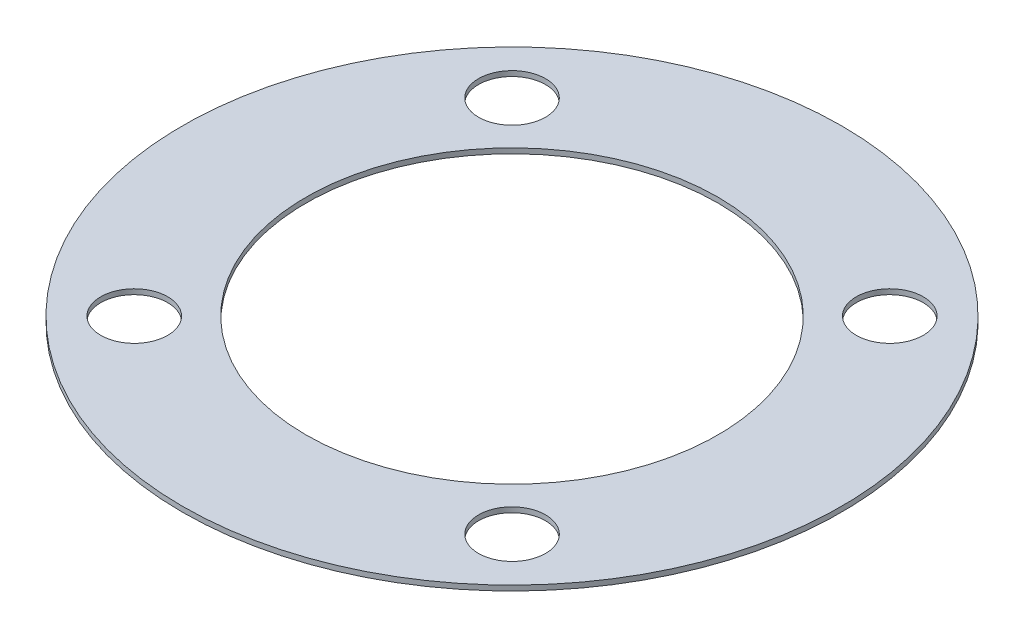
SolidWorks part; units mm, degrees
ref_plane "Front Plane" through (0, 0, 0) normal (0, 0, 1) x (1, 0, 0)
ref_plane "Top Plane" through (0, 0, 0) normal (0, 1, 0) x (1, 0, 0)
ref_plane "Right Plane" through (0, 0, 0) normal (1, 0, 0) x (0, 0, -1)
sketch "Sketch1" plane through (0, 0, 0) normal (0, 1, 0) x (1, 0, 0)
  circle A0 centre (0, 0) radius 32
  dimension "D1" = 64
extrude "Boss-Extrude1" add sketch "Sketch1" along normal blind 0.5
sketch "Sketch2" plane through (0, 0.5, 0) normal (0, 1, 0) x (1, 0, 0)
  circle A0 centre (0, 0) radius 20
  dimension "D1" = 40
extrude "Cut-Extrude1" cut sketch "Sketch2" against normal through all
sketch "Sketch3" plane through (0, 0.5, 0) normal (0, 1, 0) x (1, 0, 0)
  circle A1 centre (18.3425, 18.3393) radius 3.25
  circle A2 centre (-18.3393, 18.3425) radius 3.25
  circle A3 centre (-18.3393, -18.3425) radius 3.25
  circle A4 centre (18.3425, -18.3393) radius 3.25
  dimension "D2" = 6.5
  dimension "D4" = 6.5
  dimension "D6" = 6.5
  dimension "D7" = 6.5
extrude "Cut-Extrude2" cut sketch "Sketch3" against normal through all
